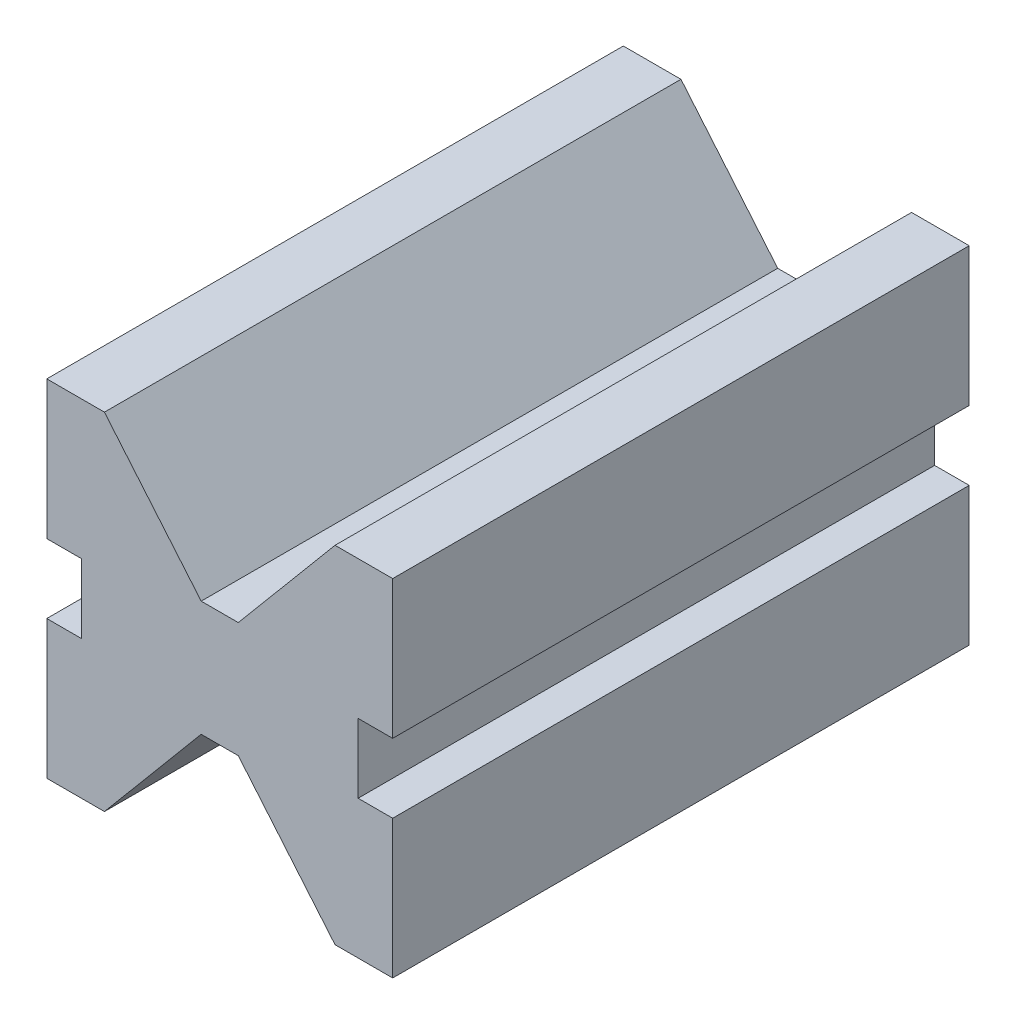
SolidWorks part; units mm, degrees
material "1060 Alloy"
ref_plane "Front Plane" through (0, 0, 0) normal (0, 0, 1) x (1, 0, 0)
ref_plane "Top Plane" through (0, 0, 0) normal (0, 1, 0) x (1, 0, 0)
ref_plane "Right Plane" through (0, 0, 0) normal (1, 0, 0) x (0, 0, -1)
sketch "Sketch2" plane through (0, 0, 0) normal (0, 0, 1) x (1, 0, 0)
  line L0 (0, 0) -> (10, 0)
  line L1 (10, 0) -> (26.782, 20)
  line L2 (26.782, 20) -> (33.218, 20)
  line L3 (0, 0) -> (0, 24)
  line L4 (0, 24) -> (6, 24)
  line L5 (6, 24) -> (6, 36)
  line L6 (6, 36) -> (0, 36)
  line L7 (0, 36) -> (0, 60)
  line L8 (0, 60) -> (10, 60)
  line L9 (10, 60) -> (26.782, 40)
  line L10 (26.782, 40) -> (33.218, 40)
  line L11 (30, 65.0934) -> (30, -7.2326) construction
  line L12 (10, 60) -> (40.5433, 60) construction
  line L13 (50, 60) -> (33.218, 40)
  line L14 (60, 60) -> (50, 60)
  line L15 (60, 36) -> (60, 60)
  line L16 (54, 36) -> (60, 36)
  line L17 (54, 24) -> (54, 36)
  line L18 (60, 24) -> (54, 24)
  line L19 (60, 0) -> (60, 24)
  line L20 (50, 0) -> (33.218, 20)
  line L21 (60, 0) -> (50, 0)
  point P18 (30, 20)
  point P19 (30, 40)
  dimension "D1" = 60
  dimension "D2" = 24
  dimension "D3" = 24
  dimension "D4" = 6
  dimension "D5" = 20
  dimension "D6" = 20
  dimension "D7" = 30
  dimension "D8" = 50
  dimension "D9" = 20
extrude "Boss-Extrude1" add sketch "Sketch2" against normal blind 100
